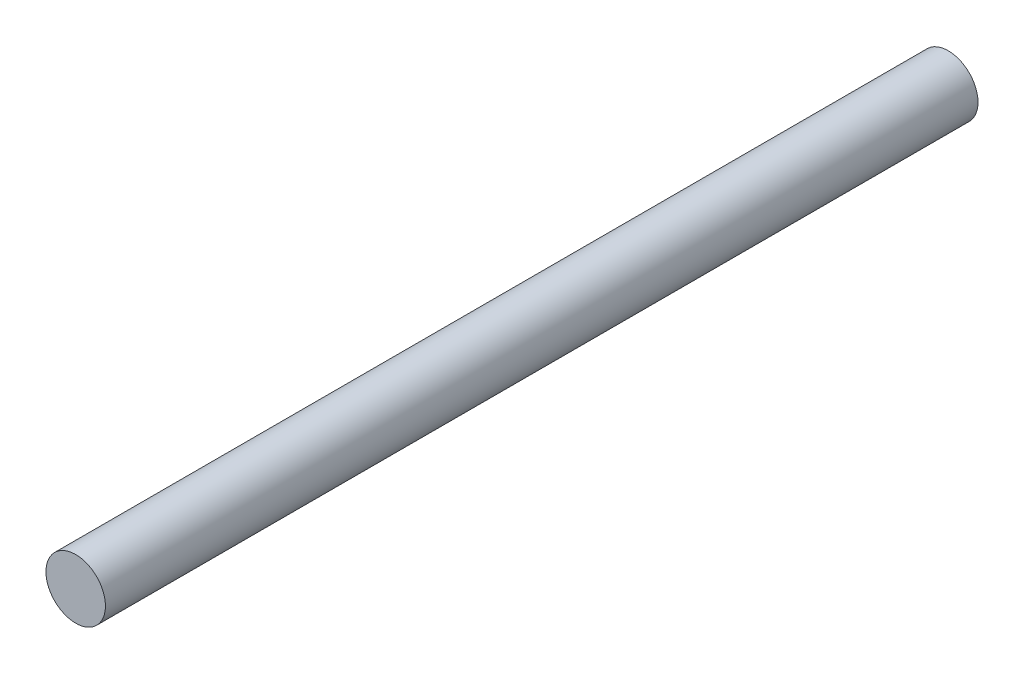
SolidWorks part; units mm, degrees
material "PET"
ref_plane "Alzado" through (0, 0, 0) normal (0, 0, 1) x (1, 0, 0)
ref_plane "Planta" through (0, 0, 0) normal (0, 1, 0) x (1, 0, 0)
ref_plane "Vista lateral" through (0, 0, 0) normal (1, 0, 0) x (0, 0, -1)
sketch "Croquis1" plane through (0, 0, 0) normal (0, 0, 1) x (1, 0, 0)
  circle A0 centre (0, 0) radius 1.5
  dimension "D1" = 3
extrude "Saliente-Extruir1" add sketch "Croquis1" along normal blind 44
